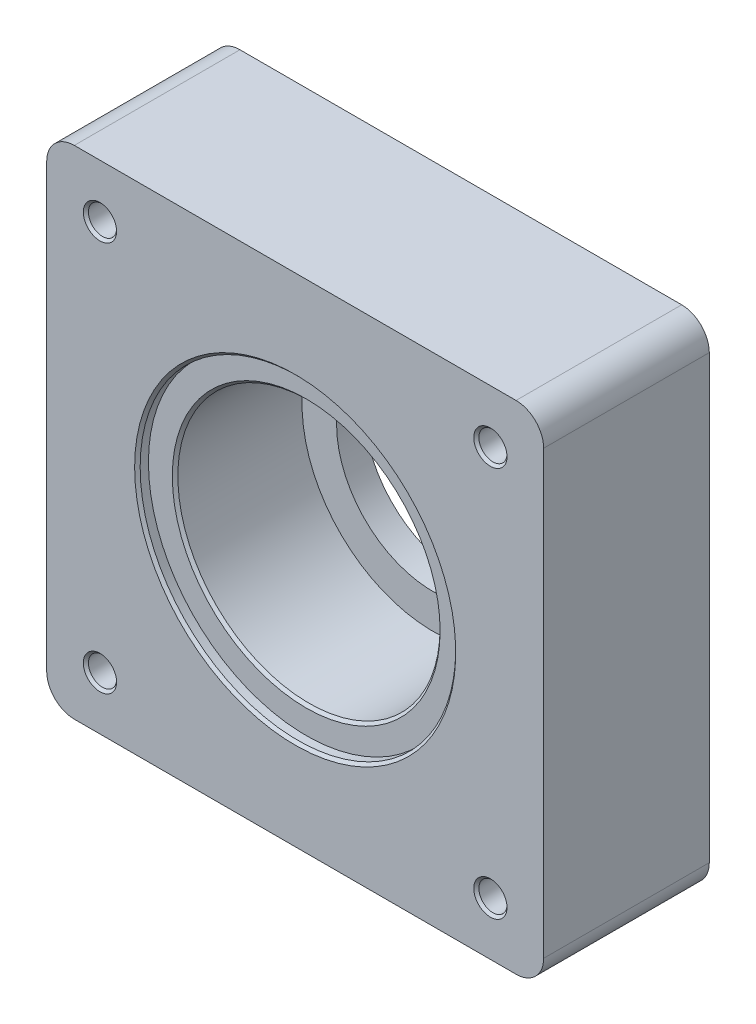
SolidWorks part; units mm, degrees
ref_plane "Front Plane" through (0, 0, 0) normal (0, 0, 1) x (1, 0, 0)
ref_plane "Top Plane" through (0, 0, 0) normal (0, 1, 0) x (1, 0, 0)
ref_plane "Right Plane" through (0, 0, 0) normal (1, 0, 0) x (0, 0, -1)
sketch "Sketch1" plane through (0, 0, 0) normal (0, 0, 1) x (1, 0, 0)
  line L1 (-80, -90) -> (80, -90)
  line L2 (-90, -80) -> (-90, 80)
  line L3 (-80, 90) -> (80, 90)
  line L4 (90, -80) -> (90, 80)
  line L5 (-90, -90) -> (90, 90) construction
  line L6 (-90, 90) -> (90, -90) construction
  arc A0 (-80, -90) -> (-90, -80) centre (-80, -80) cw
  arc A1 (80, -90) -> (90, -80) centre (80, -80) ccw
  arc A2 (-90, 80) -> (-80, 90) centre (-80, 80) cw
  arc A3 (80, 90) -> (90, 80) centre (80, 80) cw
  circle A4 centre (0, 0) radius 35
  point P0 (0, 0)
  dimension "D2" = 10
  dimension "D3" = 70
  dimension "D1" = 180
extrude "Boss-Extrude1" add sketch "Sketch1" along normal blind 60
sketch "Sketch2" plane through (0, 0, 60) normal (0, 0, 1) x (1, 0, 0)
  line L1 (-70.7107, -70.7107) -> (70.7107, -70.7107) construction
  line L2 (-70.7107, -70.7107) -> (-70.7107, 70.7107) construction
  line L3 (-70.7107, 70.7107) -> (70.7107, 70.7107) construction
  line L4 (70.7107, -70.7107) -> (70.7107, 70.7107) construction
  line L5 (-70.7107, -70.7107) -> (70.7107, 70.7107) construction
  line L6 (-70.7107, 70.7107) -> (70.7107, -70.7107) construction
  point P0 (0, 0)
  dimension "D1" = 200
hole_wizard "M12x1.75 Tapped Hole1" positions "Sketch3" profile "Sketch4" tap size "M12x1.75" standard "ANSI Metric"
sketch "Sketch3" plane through (0, 0, 60) normal (0, 0, 1) x (1, 0, 0)
  point P0 (-70.7107, 70.7107)
  point P3 (70.7107, 70.7107)
  point P6 (70.7107, -70.7107)
  point P9 (-70.7107, -70.7107)
sketch "Sketch4" plane through (-70.7107, 70.7107, 60) normal (1, 0, 0) x (0, -1, 0)
  line L0 (0, 0) -> (0, 38.3144)
  line L1 (0, 38.3144) -> (5.1, 35.25)
  line L2 (5.1, 35.25) -> (5.1, 0.925)
  line L3 (5.1, 0.925) -> (6.025, 0)
  line L5 (6.025, 0) -> (0, 0)
  line L6 (-5.1, 0.925) -> (-6.025, 0) construction
  line L10 (0, 38.3144) -> (-5.1, 35.25) construction
  line L11 (0, -6.35) -> (0, 107.95) construction
  dimension "Tap Drill Dia." = 10.2
  dimension "Tap Drill Depth" = 35.25
  dimension "Near C'Sink Dia." = 12.05
  dimension "Near C'Sink Angle" = 90
  dimension "Drill Angle" = 118
cosmetic thread "Hole Thread1" parameters "D1"=30, "D2"=12
cosmetic thread "Hole Thread2" parameters "D1"=30, "D2"=12
cosmetic thread "Hole Thread3" parameters "D1"=30, "D2"=12
cosmetic thread "Hole Thread4" parameters "D1"=30, "D2"=12
sketch "Sketch5" plane through (0, 0, 60) normal (0, 0, 1) x (1, 0, 0)
  circle A0 centre (0, 0) radius 57.15
  dimension "D1" = 114.3
extrude "Cut-Extrude1" cut sketch "Sketch5" against normal blind 4
sketch "Sketch6" plane through (0, 0, 0) normal (0, 0, -1) x (-1, 0, 0)
  line L0 (0, 0) -> (-39, 67.55) construction
  circle A0 centre (0, 0) radius 78 construction
  dimension "D1" = 156
  dimension "D2" = 30
hole_wizard "M12 Tapped Hole1" positions "Sketch7" profile "Sketch8" tap size "M12" standard "ISO"
sketch "Sketch7" plane through (0, 0, 0) normal (0, 0, -1) x (-1, 0, 0)
  point P0 (-39, 67.55)
sketch "Sketch8" plane through (39, 67.55, 0) normal (1, 0, 0) x (0, 1, 0)
  line L0 (0, 0) -> (0, 38.3144)
  line L1 (0, 38.3144) -> (5.1, 35.25)
  line L2 (5.1, 35.25) -> (5.1, 0.925)
  line L3 (5.1, 0.925) -> (6.025, 0)
  line L5 (6.025, 0) -> (0, 0)
  line L6 (-5.1, 0.925) -> (-6.025, 0) construction
  line L10 (0, 38.3144) -> (-5.1, 35.25) construction
  line L11 (0, -6.35) -> (0, 107.95) construction
  dimension "Tap Drill Dia." = 10.2
  dimension "Tap Drill Depth" = 35.25
  dimension "Near C'Sink Dia." = 12.05
  dimension "Near C'Sink Angle" = 90
  dimension "Drill Angle" = 118
cosmetic thread "Hole Thread5" parameters "D1"=30, "D2"=12
pattern_circular "CirPattern1" count 6 over 360 about axis through (0, 0, 0) along (0, 0, 1) of "M12 Tapped Hole1"
cosmetic thread "Hole Thread6" parameters "D1"=30, "D2"=12
cosmetic thread "Hole Thread7" parameters "D1"=30, "D2"=12
cosmetic thread "Hole Thread8" parameters "D1"=30, "D2"=12
cosmetic thread "Hole Thread9" parameters "D1"=30, "D2"=12
cosmetic thread "Hole Thread10" parameters "D1"=30, "D2"=12
sketch "Sketch9" plane through (0, 0, 60) normal (0, 0, 1) x (1, 0, 0)
  circle A0 centre (0, 0) radius 47.5
  dimension "D1" = 95
extrude "Cut-Extrude2" cut sketch "Sketch9" against normal blind 50
chamfer "Chamfer1" distance 1 angle 45 2 edges at (57.15, 0, 60) (47.5, 0, 56)
sketch "Sketch10" plane through (0, 0, 0) normal (0, 0, -1) x (-1, 0, 0)
  line L0 (-29.8493, 72.0626) -> (29.8493, 72.0626) construction
  line L1 (0, 0) -> (78, 0) construction
  circle A0 centre (0, 0) radius 78 construction
  circle A1 centre (-72.0626, 29.8493) radius 6.5 construction
  circle A2 centre (-29.8493, 72.0626) radius 6.5 construction
  circle A3 centre (29.8493, 72.0626) radius 6.5 construction
  circle A4 centre (72.0626, 29.8493) radius 6.5 construction
  circle A9 centre (72.0626, -29.8493) radius 6.5 construction
  circle A10 centre (29.8493, -72.0626) radius 6.5 construction
  circle A11 centre (-29.8493, -72.0626) radius 6.5 construction
  circle A12 centre (-72.0626, -29.8493) radius 6.5 construction
  point P21 (0, 0)
  dimension "D1" = 156
  dimension "D2" = 13
  dimension "D3" = 8
hole_wizard "M12 Tapped Hole2" positions "3DSketch1" profile "Sketch11" tap size "M12" standard "ISO"
sketch3d "3DSketch1"
  point P0 (29.8493, 72.0626, 0)
  point P3 (-29.8493, 72.0626, 0)
  point P6 (-72.0626, 29.8493, 0)
  point P9 (-72.0626, -29.8493, 0)
  point P12 (-29.8493, -72.0626, 0)
  point P15 (29.8493, -72.0626, 0)
  point P18 (72.0626, -29.8493, 0)
  point P21 (72.0626, 29.8493, 0)
sketch "Sketch11" plane through (29.8493, 72.0626, 0) normal (1, 0, 0) x (0, 1, 0)
  line L0 (0, 0) -> (0, 38.3144)
  line L1 (0, 38.3144) -> (5.1, 35.25)
  line L2 (5.1, 35.25) -> (5.1, 0.925)
  line L3 (5.1, 0.925) -> (6.025, 0)
  line L5 (6.025, 0) -> (0, 0)
  line L6 (-5.1, 0.925) -> (-6.025, 0) construction
  line L10 (0, 38.3144) -> (-5.1, 35.25) construction
  line L11 (0, -6.35) -> (0, 107.95) construction
  dimension "Tap Drill Dia." = 10.2
  dimension "Tap Drill Depth" = 35.25
  dimension "Near C'Sink Dia." = 12.05
  dimension "Near C'Sink Angle" = 90
  dimension "Drill Angle" = 118
cosmetic thread "Hole Thread11" parameters "D1"=30, "D2"=12
cosmetic thread "Hole Thread12" parameters "D1"=30, "D2"=12
cosmetic thread "Hole Thread13" parameters "D1"=30, "D2"=12
cosmetic thread "Hole Thread14" parameters "D1"=30, "D2"=12
cosmetic thread "Hole Thread15" parameters "D1"=30, "D2"=12
cosmetic thread "Hole Thread16" parameters "D1"=30, "D2"=12
cosmetic thread "Hole Thread17" parameters "D1"=30, "D2"=12
cosmetic thread "Hole Thread18" parameters "D1"=30, "D2"=12
